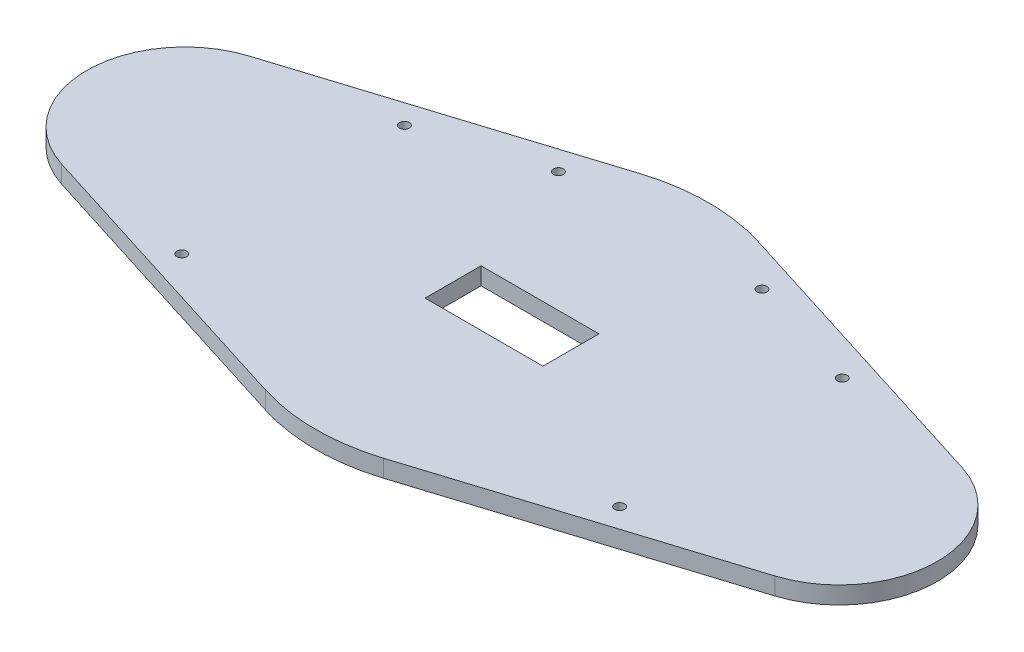
SolidWorks part; units mm, degrees
ref_plane "Front Plane" through (0, 0, 0) normal (0, 0, 1) x (1, 0, 0)
ref_plane "Top Plane" through (0, 0, 0) normal (0, 1, 0) x (1, 0, 0)
ref_plane "Right Plane" through (0, 0, 0) normal (1, 0, 0) x (0, 0, -1)
sketch "Sketch1" plane through (0, 0, 0) normal (0, 1, 0) x (1, 0, 0)
  line L0 (-92.2096, 24.2277) -> (-15.2553, 48.4553)
  line L1 (92.2096, 24.2277) -> (15.2553, 48.4553)
  line L2 (-92.2096, -24.2277) -> (-15.2553, -48.4553)
  line L3 (92.2096, -24.2277) -> (15.2553, -48.4553)
  line L4 (-109.982, 0) -> (-46.482, 0) construction
  line L5 (46.482, 0) -> (109.982, 0) construction
  line L6 (0, 46.482) -> (0, 7.239) construction
  line L7 (-15.24, 7.239) -> (15.24, 7.239)
  line L8 (-15.24, 7.239) -> (-15.24, -7.239)
  line L9 (-15.24, -7.239) -> (15.24, -7.239)
  line L10 (15.24, 7.239) -> (15.24, -7.239)
  line L11 (46.482, 0) -> (15.24, 0) construction
  line L12 (-26.3141, 38.3164) -> (26.3141, 38.3164) construction
  line L13 (-56.6034, 28.7804) -> (56.6034, 28.7804) construction
  line L14 (-56.6034, 28.7804) -> (-56.6034, -28.7804) construction
  line L15 (-56.6034, -28.7804) -> (56.6034, -28.7804) construction
  line L16 (56.6034, 28.7804) -> (56.6034, -28.7804) construction
  arc A0 (-15.2553, -48.4553) -> (15.2553, -48.4553) centre (0, 0) ccw
  arc A1 (-92.2096, 24.2277) -> (-92.2096, -24.2277) centre (-84.582, 0) ccw
  arc A2 (92.2096, -24.2277) -> (92.2096, 24.2277) centre (84.582, 0) ccw
  arc A3 (15.2553, 48.4553) -> (-15.2553, 48.4553) centre (0, 0) ccw
  circle A4 centre (0, 0) radius 46.482 construction
  circle A5 centre (0, 0) radius 63.5 construction
  circle A6 centre (-56.6034, 28.7804) radius 1.27
  circle A7 centre (-56.6034, -28.7804) radius 1.27
  circle A8 centre (56.6034, -28.7804) radius 1.27
  circle A9 centre (56.6034, 28.7804) radius 1.27
  circle A10 centre (-26.3141, 38.3164) radius 1.27
  circle A11 centre (26.3141, 38.3164) radius 1.27
  dimension "D1" = 63.5
  dimension "D2" = 92.964
  dimension "D3" = 25.4
  dimension "D4" = 50.8
  dimension "D7" = 127
  dimension "D9" = 2.54
  dimension "D5" = 30.48
  dimension "D6" = 14.478
  dimension "D8" = 6.35
  dimension "D10" = 6.35
extrude "Boss-Extrude1" add sketch "Sketch1" along normal blind 4.4958
